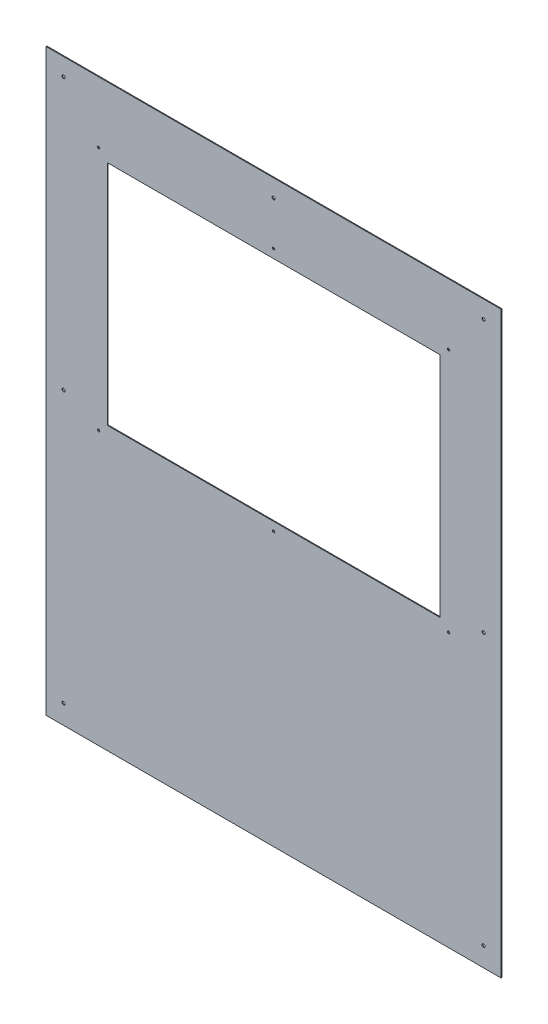
SolidWorks part; units mm, degrees
material "1023 Carbon Steel Sheet (SS)"
ref_plane "Front Plane" through (0, 0, 0) normal (0, 0, 1) x (1, 0, 0)
ref_plane "Top Plane" through (0, 0, 0) normal (0, 1, 0) x (1, 0, 0)
ref_plane "Right Plane" through (0, 0, 0) normal (1, 0, 0) x (0, 0, -1)
sketch "Sketch1" plane through (0, 0, 0) normal (0, 0, 1) x (1, 0, 0)
  line L1 (0, 0) -> (660.4, 0)
  line L2 (0, 0) -> (0, 840.74)
  line L3 (0, 840.74) -> (660.4, 840.74)
  line L4 (660.4, 0) -> (660.4, 840.74)
  dimension "D1" = 840.74
  dimension "D2" = 660.4
extrude "Boss-Extrude1" add sketch "Sketch1" along normal blind 1.2192
sketch "Sketch2" plane through (0, 0, 1.2192) normal (0, 0, 1) x (1, 0, 0)
  line L0 (660.4, 0) -> (660.4, 840.74) construction
  line L1 (25.4, 815.34) -> (635, 815.34) construction
  line L2 (25.4, 815.34) -> (25.4, 27.94) construction
  line L3 (25.4, 27.94) -> (635, 27.94) construction
  line L4 (635, 815.34) -> (635, 27.94) construction
  line L5 (660.4, 840.74) -> (0, 840.74) construction
  line L6 (0, 840.74) -> (0, 0) construction
  point P12 (25.4, 421.64)
  point P13 (25.4, 815.34)
  point P14 (25.4, 27.94)
  point P15 (330.2, 815.34)
  point P16 (635, 421.64)
  point P17 (635, 815.34)
  point P19 (635, 27.94)
  dimension "D1" = 25.4
  dimension "D2" = 25.4
  dimension "D3" = 25.4
  dimension "D4" = 393.7
  dimension "D5" = 393.7
hole_wizard "#8 Clearance Hole1" positions "Sketch4" profile "Sketch3" hole size "#8" standard "ANSI Inch" end condition through all
sketch "Sketch4" plane through (0, 0, 1.2192) normal (0, 0, 1) x (1, 0, 0)
  point P0 (25.4, 815.34)
  point P2 (330.2, 815.34)
  point P4 (635, 815.34)
  point P11 (25.4, 421.64)
  point P14 (25.4, 27.94)
  point P17 (635, 27.94)
  point P20 (635, 421.64)
sketch "Sketch3" plane through (25.4, 815.34, 1.2192) normal (1, 0, 0) x (0, -1, 0)
  line L0 (0, 0) -> (0, 1.2192)
  line L1 (0, 1.2192) -> (2.2479, 1.2192)
  line L2 (2.2479, 1.2192) -> (2.2479, 0)
  line L5 (2.2479, 0) -> (0, 0)
  line L11 (0, -6.35) -> (0, 107.95) construction
  dimension "Thru Hole Dia." = 4.4958
  dimension "Thru Hole Depth" = 1.2192
sketch "Sketch5" plane through (0, 0, 1.2192) normal (0, 0, 1) x (1, 0, 0)
  line L0 (0, 840.74) -> (0, 0) construction
  line L1 (88.9, 739.14) -> (571.5, 739.14)
  line L2 (88.9, 739.14) -> (88.9, 408.94)
  line L3 (88.9, 408.94) -> (571.5, 408.94)
  line L4 (571.5, 739.14) -> (571.5, 408.94)
  line L8 (660.4, 840.74) -> (0, 840.74) construction
  dimension "D1" = 330.2
  dimension "D2" = 482.6
  dimension "D3" = 88.9
  dimension "D4" = 101.6
extrude "Cut-Extrude1" cut sketch "Sketch5" against normal blind 2.54
sketch "Sketch6" plane through (0, 0, 1.2192) normal (0, 0, 1) x (1, 0, 0)
  line L0 (571.5, 739.14) -> (88.9, 739.14) construction
  line L1 (76.2, 751.84) -> (584.2, 751.84)
  line L2 (76.2, 751.84) -> (76.2, 396.24)
  line L3 (76.2, 396.24) -> (584.2, 396.24)
  line L4 (584.2, 751.84) -> (584.2, 396.24)
  line L5 (88.9, 408.94) -> (571.5, 408.94) construction
  line L6 (88.9, 739.14) -> (88.9, 408.94) construction
  line L7 (571.5, 408.94) -> (571.5, 739.14) construction
  point P12 (330.2, 751.84)
  point P13 (76.2, 751.84)
  point P14 (330.2, 396.24)
  point P15 (584.2, 751.84)
  point P16 (584.2, 396.24)
  point P18 (76.2, 396.24)
  dimension "D1" = 12.7
  dimension "D2" = 12.7
  dimension "D3" = 12.7
  dimension "D4" = 12.7
hole_wizard "Tap Drill for #8-32 Tap1" positions "Sketch8" profile "Sketch7" hole size "#8-32" standard "ANSI Inch"
sketch "Sketch8" plane through (0, 0, 1.2192) normal (0, 0, 1) x (1, 0, 0)
  point P0 (76.2, 751.84)
  point P3 (330.2, 751.84)
  point P6 (584.2, 751.84)
  point P9 (584.2, 396.24)
  point P12 (330.2, 396.24)
  point P15 (76.2, 396.24)
sketch "Sketch7" plane through (76.2, 751.84, 1.2192) normal (1, 0, 0) x (0, -1, 0)
  line L0 (0, 0) -> (0, 26.4378)
  line L1 (0, 26.4378) -> (1.7272, 25.4)
  line L2 (1.7272, 25.4) -> (1.7272, 0)
  line L5 (1.7272, 0) -> (0, 0)
  line L10 (0, 26.4378) -> (-1.7272, 25.4) construction
  line L11 (0, -6.35) -> (0, 107.95) construction
  dimension "Hole Dia." = 3.4544
  dimension "Hole Depth" = 25.4
  dimension "Drill Angle" = 118
equation "\"h\"=33.1"
equation "\"b\"=26"
equation "\"d\"=1"
